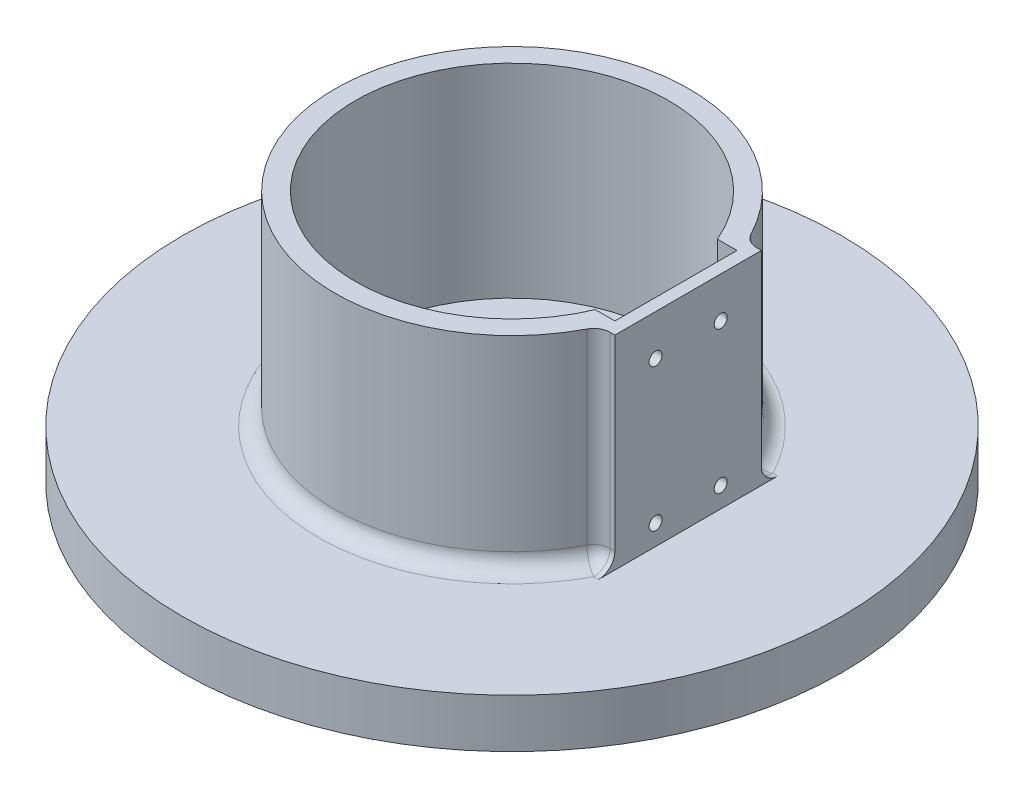
SolidWorks part; units mm, degrees
ref_plane "Front Plane" through (0, 0, 0) normal (0, 0, 1) x (1, 0, 0)
ref_plane "Top Plane" through (0, 0, 0) normal (0, 1, 0) x (1, 0, 0)
ref_plane "Right Plane" through (0, 0, 0) normal (1, 0, 0) x (0, 0, -1)
sketch "Sketch1" plane through (0, 0, 0) normal (0, 1, 0) x (1, 0, 0)
  line L0 (105.5, 0) -> (105.5, 60.5) construction
  line L1 (0, 0) -> (211, 0) construction
  line L2 (0, 0) -> (0, 121) construction
  line L3 (0, 121) -> (211, 121) construction
  line L4 (211, 0) -> (211, 121) construction
  line L5 (105.5, 60.5) -> (0, 60.5) construction
  circle A0 centre (105.5, 60.5) radius 81
  dimension "D3" = 162
  dimension "D1" = 211
  dimension "D2" = 121
extrude "Boss-Extrude1" add sketch "Sketch1" along normal blind 12
sketch "Sketch2" plane through (0, 0, 0) normal (0, -1, 0) x (1, 0, 0)
  circle A0 centre (105.5, -60.5) radius 76
  circle A1 centre (105.5, -60.5) radius 81 construction
  dimension "D1" = 5
extrude "Cut-Extrude1" cut sketch "Sketch2" against normal blind 7
sketch "Sketch3" plane through (0, 12, 0) normal (0, 1, 0) x (1, 0, 0)
  circle A0 centre (105.5, 60.5) radius 32
  circle A1 centre (105.5, 60.5) radius 81 construction
  point P3 (0, 0)
  dimension "D1" = 64
extrude "Cut-Extrude2" cut sketch "Sketch3" against normal through all
sketch "Sketch4" plane through (0, 12, 0) normal (0, 1, 0) x (1, 0, 0)
  line L0 (105.5, 60.5) -> (138.7754, 60.5) construction
  line L4 (138.7754, 75.5) -> (184.4747, 75.5)
  line L5 (138.7754, 75.5) -> (138.7754, 45.5)
  line L6 (138.7754, 45.5) -> (184.4747, 45.5)
  line L7 (184.4747, 75.5) -> (184.4747, 45.5)
  line L10 (145.7754, 75.5) -> (145.7754, 45.5)
  line L11 (148.7754, 78.5) -> (148.7754, 42.5)
  line L12 (145.1011, 78.5) -> (184.4747, 78.5)
  line L14 (145.1011, 42.5) -> (184.4747, 42.5)
  line L15 (184.4747, 78.5) -> (184.4747, 42.5)
  circle A0 centre (105.5, 60.5) radius 36.5 construction
  circle A1 centre (105.5, 60.5) radius 38.5
  circle A2 centre (105.5, 60.5) radius 81 construction
  circle A3 centre (105.5, 60.5) radius 32 construction
  arc A4 (148.7754, 64.9151) -> (148.7754, 56.0849) centre (105.5, 60.5) ccw
  dimension "D1" = 73
  dimension "D3" = 7
  dimension "D7" = 5
  dimension "D2" = 30
  dimension "D4" = 7
  dimension "D5" = 3
  dimension "D6" = 3
extrude "Boss-Extrude2" add sketch "Sketch4" along normal blind 50 contours A4 L6 A1 L4 | L6 A4 L11 L4 L10 | A4 L4 L11 L12 | A4 L11 L4 | A4 L6 L11 | A4 L14 L11 L6
sketch "Sketch5" plane through (148.7754, 0, 0) normal (1, 0, 0) x (0, 0, -1)
  line L0 (60.5, 62) -> (60.5, 52) construction
  line L1 (52.5, 52) -> (68.5, 52) construction
  line L2 (52.5, 52) -> (52.5, 17) construction
  line L3 (52.5, 17) -> (68.5, 17) construction
  line L4 (68.5, 52) -> (68.5, 17) construction
  line L9 (78.5, 62) -> (42.5, 62) construction
  line L10 (78.5, 12) -> (42.5, 12) construction
  circle A0 centre (52.5, 52) radius 1.6
  circle A1 centre (68.5, 52) radius 1.6
  circle A2 centre (68.5, 17) radius 1.6
  circle A3 centre (52.5, 17) radius 1.6
  dimension "D4" = 3.2
  dimension "D1" = 16
  dimension "D2" = 35
  dimension "D3" = 5
extrude "Cut-Extrude3" cut sketch "Sketch5" against normal blind 6
fillet "Fillet1" radius 4 5 edges at (146.9383, 12, -78.5) (146.9383, 12, -42.5) (62, 12, -60.5) (145.1011, 37, -78.5) (145.1011, 37, -42.5)
fillet "Fillet2" radius 2 1 edges at (105.5, 7, -136.5)
